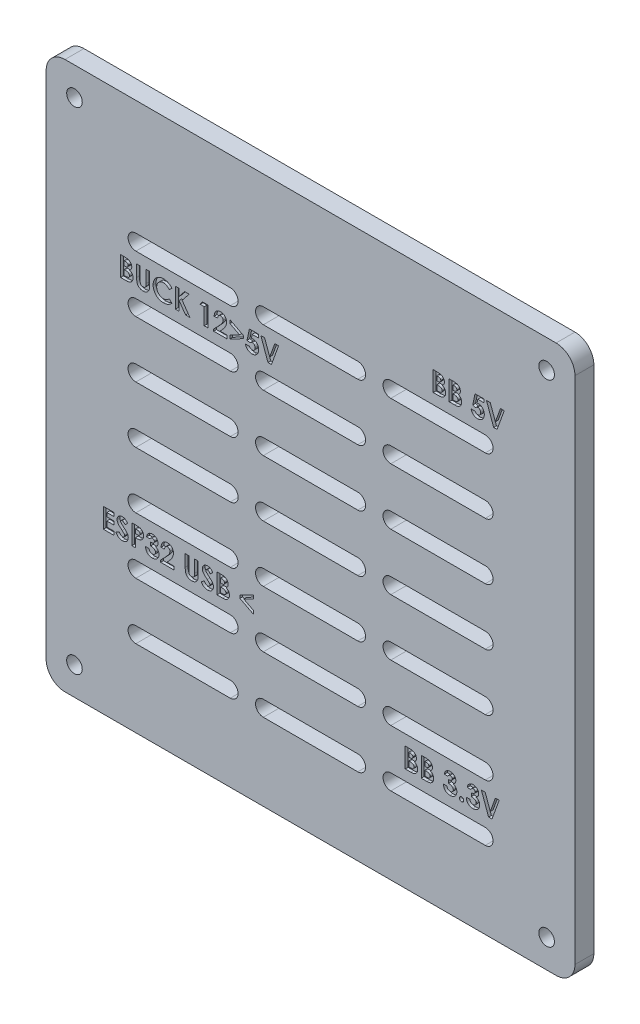
SolidWorks part; units mm, degrees
ref_plane "Front Plane" through (0, 0, 0) normal (0, 0, 1) x (1, 0, 0)
ref_plane "Top Plane" through (0, 0, 0) normal (0, 1, 0) x (1, 0, 0)
ref_plane "Right Plane" through (0, 0, 0) normal (1, 0, 0) x (0, 0, -1)
sketch "Sketch1" plane through (0, 0, 0) normal (0, 0, 1) x (1, 0, 0)
  line L0 (-52, 40) -> (52, 40)
  line L1 (56, 44) -> (56, 152)
  line L2 (52, 156) -> (-52, 156)
  line L3 (-56, 152) -> (-56, 44)
  arc A0 (-56, 44) -> (-52, 40) centre (-52, 44) ccw
  arc A1 (52, 40) -> (56, 44) centre (52, 44) ccw
  arc A2 (56, 152) -> (52, 156) centre (52, 152) ccw
  arc A3 (-52, 156) -> (-56, 152) centre (-52, 152) ccw
extrude "Plate" add sketch "Sketch1" along normal blind 4
sketch "Sketch2" plane through (0, 0, 0) normal (0, 0, 1) x (1, 0, 0)
  line L0 (-37, 58) -> (-17, 58) construction
  line L1 (-37, 59.65) -> (-17, 59.65)
  line L2 (-37, 56.35) -> (-17, 56.35)
  line L3 (-10, 58) -> (10, 58) construction
  line L4 (-10, 59.65) -> (10, 59.65)
  line L5 (-10, 56.35) -> (10, 56.35)
  line L6 (17, 58) -> (37, 58) construction
  line L7 (17, 59.65) -> (37, 59.65)
  line L8 (17, 56.35) -> (37, 56.35)
  line L9 (-37, 70) -> (-17, 70) construction
  line L10 (-37, 71.65) -> (-17, 71.65)
  line L11 (-37, 68.35) -> (-17, 68.35)
  line L12 (-10, 70) -> (10, 70) construction
  line L13 (-10, 71.65) -> (10, 71.65)
  line L14 (-10, 68.35) -> (10, 68.35)
  line L15 (17, 70) -> (37, 70) construction
  line L16 (17, 71.65) -> (37, 71.65)
  line L17 (17, 68.35) -> (37, 68.35)
  line L18 (-37, 82) -> (-17, 82) construction
  line L19 (-37, 83.65) -> (-17, 83.65)
  line L20 (-37, 80.35) -> (-17, 80.35)
  line L21 (-10, 82) -> (10, 82) construction
  line L22 (-10, 83.65) -> (10, 83.65)
  line L23 (-10, 80.35) -> (10, 80.35)
  line L24 (17, 82) -> (37, 82) construction
  line L25 (17, 83.65) -> (37, 83.65)
  line L26 (17, 80.35) -> (37, 80.35)
  line L27 (-37, 94) -> (-17, 94) construction
  line L28 (-37, 95.65) -> (-17, 95.65)
  line L29 (-37, 92.35) -> (-17, 92.35)
  line L30 (-10, 94) -> (10, 94) construction
  line L31 (-10, 95.65) -> (10, 95.65)
  line L32 (-10, 92.35) -> (10, 92.35)
  line L33 (17, 94) -> (37, 94) construction
  line L34 (17, 95.65) -> (37, 95.65)
  line L35 (17, 92.35) -> (37, 92.35)
  line L36 (-37, 106) -> (-17, 106) construction
  line L37 (-37, 107.65) -> (-17, 107.65)
  line L38 (-37, 104.35) -> (-17, 104.35)
  line L39 (-10, 106) -> (10, 106) construction
  line L40 (-10, 107.65) -> (10, 107.65)
  line L41 (-10, 104.35) -> (10, 104.35)
  line L42 (17, 106) -> (37, 106) construction
  line L43 (17, 107.65) -> (37, 107.65)
  line L44 (17, 104.35) -> (37, 104.35)
  line L45 (-37, 118) -> (-17, 118) construction
  line L46 (-37, 119.65) -> (-17, 119.65)
  line L47 (-37, 116.35) -> (-17, 116.35)
  line L48 (-10, 118) -> (10, 118) construction
  line L49 (-10, 119.65) -> (10, 119.65)
  line L50 (-10, 116.35) -> (10, 116.35)
  line L51 (17, 118) -> (37, 118) construction
  line L52 (17, 119.65) -> (37, 119.65)
  line L53 (17, 116.35) -> (37, 116.35)
  line L54 (-37, 130) -> (-17, 130) construction
  line L55 (-37, 131.65) -> (-17, 131.65)
  line L56 (-37, 128.35) -> (-17, 128.35)
  line L57 (-10, 130) -> (10, 130) construction
  line L58 (-10, 131.65) -> (10, 131.65)
  line L59 (-10, 128.35) -> (10, 128.35)
  line L60 (17, 130) -> (37, 130) construction
  line L61 (17, 131.65) -> (37, 131.65)
  line L62 (17, 128.35) -> (37, 128.35)
  circle A0 centre (-50, 46) radius 1.65
  circle A1 centre (50, 46) radius 1.65
  circle A2 centre (-50, 150) radius 1.65
  circle A3 centre (50, 150) radius 1.65
  arc A4 (-37, 59.65) -> (-37, 56.35) centre (-37, 58) ccw
  arc A5 (-17, 56.35) -> (-17, 59.65) centre (-17, 58) ccw
  arc A6 (-10, 59.65) -> (-10, 56.35) centre (-10, 58) ccw
  arc A7 (10, 56.35) -> (10, 59.65) centre (10, 58) ccw
  arc A8 (17, 59.65) -> (17, 56.35) centre (17, 58) ccw
  arc A9 (37, 56.35) -> (37, 59.65) centre (37, 58) ccw
  arc A10 (-37, 71.65) -> (-37, 68.35) centre (-37, 70) ccw
  arc A11 (-17, 68.35) -> (-17, 71.65) centre (-17, 70) ccw
  arc A12 (-10, 71.65) -> (-10, 68.35) centre (-10, 70) ccw
  arc A13 (10, 68.35) -> (10, 71.65) centre (10, 70) ccw
  arc A14 (17, 71.65) -> (17, 68.35) centre (17, 70) ccw
  arc A15 (37, 68.35) -> (37, 71.65) centre (37, 70) ccw
  arc A16 (-37, 83.65) -> (-37, 80.35) centre (-37, 82) ccw
  arc A17 (-17, 80.35) -> (-17, 83.65) centre (-17, 82) ccw
  arc A18 (-10, 83.65) -> (-10, 80.35) centre (-10, 82) ccw
  arc A19 (10, 80.35) -> (10, 83.65) centre (10, 82) ccw
  arc A20 (17, 83.65) -> (17, 80.35) centre (17, 82) ccw
  arc A21 (37, 80.35) -> (37, 83.65) centre (37, 82) ccw
  arc A22 (-37, 95.65) -> (-37, 92.35) centre (-37, 94) ccw
  arc A23 (-17, 92.35) -> (-17, 95.65) centre (-17, 94) ccw
  arc A24 (-10, 95.65) -> (-10, 92.35) centre (-10, 94) ccw
  arc A25 (10, 92.35) -> (10, 95.65) centre (10, 94) ccw
  arc A26 (17, 95.65) -> (17, 92.35) centre (17, 94) ccw
  arc A27 (37, 92.35) -> (37, 95.65) centre (37, 94) ccw
  arc A28 (-37, 107.65) -> (-37, 104.35) centre (-37, 106) ccw
  arc A29 (-17, 104.35) -> (-17, 107.65) centre (-17, 106) ccw
  arc A30 (-10, 107.65) -> (-10, 104.35) centre (-10, 106) ccw
  arc A31 (10, 104.35) -> (10, 107.65) centre (10, 106) ccw
  arc A32 (17, 107.65) -> (17, 104.35) centre (17, 106) ccw
  arc A33 (37, 104.35) -> (37, 107.65) centre (37, 106) ccw
  arc A34 (-37, 119.65) -> (-37, 116.35) centre (-37, 118) ccw
  arc A35 (-17, 116.35) -> (-17, 119.65) centre (-17, 118) ccw
  arc A36 (-10, 119.65) -> (-10, 116.35) centre (-10, 118) ccw
  arc A37 (10, 116.35) -> (10, 119.65) centre (10, 118) ccw
  arc A38 (17, 119.65) -> (17, 116.35) centre (17, 118) ccw
  arc A39 (37, 116.35) -> (37, 119.65) centre (37, 118) ccw
  arc A40 (-37, 131.65) -> (-37, 128.35) centre (-37, 130) ccw
  arc A41 (-17, 128.35) -> (-17, 131.65) centre (-17, 130) ccw
  arc A42 (-10, 131.65) -> (-10, 128.35) centre (-10, 130) ccw
  arc A43 (10, 128.35) -> (10, 131.65) centre (10, 130) ccw
  arc A44 (17, 131.65) -> (17, 128.35) centre (17, 130) ccw
  arc A45 (37, 128.35) -> (37, 131.65) centre (37, 130) ccw
  point P10 (-27, 58)
  point P15 (0, 58)
  point P22 (27, 58)
  point P29 (-27, 70)
  point P36 (0, 70)
  point P43 (27, 70)
  point P50 (-27, 82)
  point P57 (0, 82)
  point P64 (27, 82)
  point P71 (-27, 94)
  point P78 (0, 94)
  point P85 (27, 94)
  point P92 (-27, 106)
  point P99 (0, 106)
  point P106 (27, 106)
  point P113 (-27, 118)
  point P120 (0, 118)
  point P127 (27, 118)
  point P134 (-27, 130)
  point P141 (0, 130)
  point P148 (27, 130)
  point P155 (0, 0)
extrude "Mounting slots" cut sketch "Sketch2" along normal through all
ref_plane "P1_Front_4" through (0, 0, 4) normal (0, 0, 1) x (1, 0, 0)
sketch "Sketch3" plane through (0, 0, 4) normal (0, 0, 1) x (1, 0, 0)
  text T0 "BUCK 12>5V" font "Century Gothic" height 4.2
  text T1 "BB 5V" font "Century Gothic" height 4.2
  text T2 "ESP32 USB <" font "Century Gothic" height 4.2
  text T3 "BB 3.3V" font "Century Gothic" height 4.2
extrude "Zone labels" cut sketch "Sketch3" against normal blind 0.6
